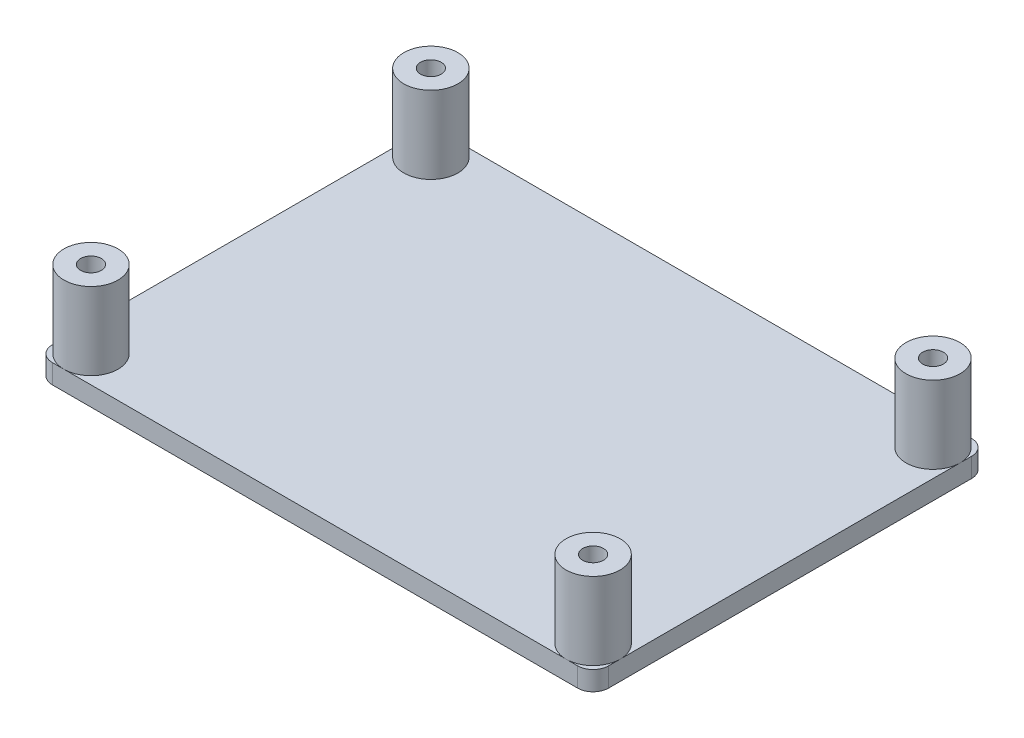
SolidWorks part; units mm, degrees
ref_plane "Front Plane" through (0, 0, 0) normal (0, 0, 1) x (1, 0, 0)
ref_plane "Top Plane" through (0, 0, 0) normal (0, 1, 0) x (1, 0, 0)
ref_plane "Right Plane" through (0, 0, 0) normal (1, 0, 0) x (0, 0, -1)
sketch "Sketch1" plane through (0, 0, 0) normal (0, 1, 0) x (1, 0, 0)
  line L1 (-45.72, -32.385) -> (45.72, -32.385)
  line L2 (-45.72, -32.385) -> (-45.72, 32.385)
  line L3 (-45.72, 32.385) -> (45.72, 32.385)
  line L4 (45.72, -32.385) -> (45.72, 32.385)
  line L5 (-45.72, -32.385) -> (45.72, 32.385) construction
  line L6 (-45.72, 32.385) -> (45.72, -32.385) construction
  line L7 (-41.275, -27.94) -> (41.275, -27.94) construction
  line L8 (-41.275, -27.94) -> (-41.275, 27.94) construction
  line L9 (-41.275, 27.94) -> (41.275, 27.94) construction
  line L10 (41.275, -27.94) -> (41.275, 27.94) construction
  line L11 (-41.275, -27.94) -> (41.275, 27.94) construction
  line L12 (-41.275, 27.94) -> (41.275, -27.94) construction
  circle A0 centre (-41.275, 27.94) radius 4.445 construction
  point P0 (0, 0)
  point P6 (0, 0)
  dimension "D1" = 91.44
  dimension "D2" = 82.55
  dimension "D3" = 55.88
extrude "Boss-Extrude1" add sketch "Sketch1" along normal blind 3.175
sketch "Sketch2" plane through (0, 3.175, 0) normal (0, 1, 0) x (1, 0, 0)
  line L1 (-41.275, -27.94) -> (41.275, -27.94) construction
  line L2 (-41.275, -27.94) -> (-41.275, 27.94) construction
  line L3 (-41.275, 27.94) -> (41.275, 27.94) construction
  line L4 (41.275, -27.94) -> (41.275, 27.94) construction
  line L5 (-41.275, -27.94) -> (41.275, 27.94) construction
  line L6 (-41.275, 27.94) -> (41.275, -27.94) construction
  circle A0 centre (-41.275, 27.94) radius 4.445
  circle A1 centre (41.275, 27.94) radius 4.445
  circle A2 centre (41.275, -27.94) radius 4.445
  circle A3 centre (-41.275, -27.94) radius 4.445
  point P0 (0, 0)
  dimension "D1" = 82.55
  dimension "D2" = 55.88
extrude "Boss-Extrude2" add sketch "Sketch2" along normal blind 12.7
sketch "Sketch3" plane through (0, 15.875, 0) normal (0, 1, 0) x (1, 0, 0)
  line L1 (-41.275, -27.94) -> (41.275, -27.94) construction
  line L2 (-41.275, -27.94) -> (-41.275, 27.94) construction
  line L3 (-41.275, 27.94) -> (41.275, 27.94) construction
  line L4 (41.275, -27.94) -> (41.275, 27.94) construction
  line L5 (-41.275, -27.94) -> (41.275, 27.94) construction
  line L6 (-41.275, 27.94) -> (41.275, -27.94) construction
  circle A1 centre (-41.275, 27.94) radius 1.7
  circle A2 centre (41.275, 27.94) radius 1.7
  circle A3 centre (41.275, -27.94) radius 1.7
  circle A4 centre (-41.275, -27.94) radius 1.7
  point P0 (0, 0)
  dimension "D1" = 3.4
extrude "Cut-Extrude1" cut sketch "Sketch3" against normal through all
fillet "Fillet1" radius 2.54 4 edges at (45.72, 1.5875, -32.385) (45.72, 1.5875, 32.385) (-45.72, 1.5875, -32.385) (-45.72, 1.5875, 32.385)
